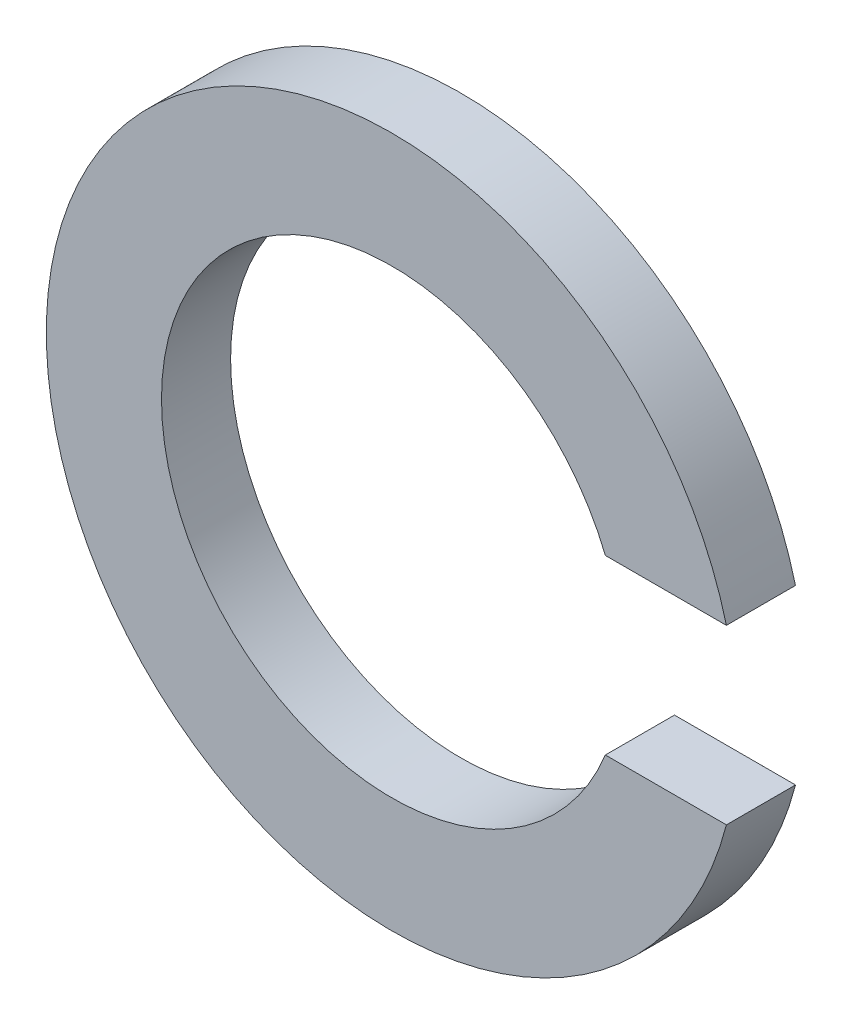
SolidWorks part; units mm, degrees
ref_plane "Front Plane" through (0, 0, 0) normal (0, 0, 1) x (1, 0, 0)
ref_plane "Top Plane" through (0, 0, 0) normal (0, 1, 0) x (1, 0, 0)
ref_plane "Right Plane" through (0, 0, 0) normal (1, 0, 0) x (0, 0, -1)
sketch "Sketch1" plane through (0, 0, 0) normal (0, 0, 1) x (1, 0, 0)
  line L0 (1.854, 0.75) -> (2.9047, 0.75)
  line L1 (1.854, -0.75) -> (2.9047, -0.75)
  line L2 (0, 0) -> (3, 0) construction
  arc A0 (1.854, 0.75) -> (1.854, -0.75) centre (0, 0) ccw
  arc A1 (2.9047, 0.75) -> (2.9047, -0.75) centre (0, 0) ccw
  dimension "D1" = 6
  dimension "D2" = 4
  dimension "D3" = 1.5
extrude "Boss-Extrude1" add sketch "Sketch1" along normal blind 0.6
